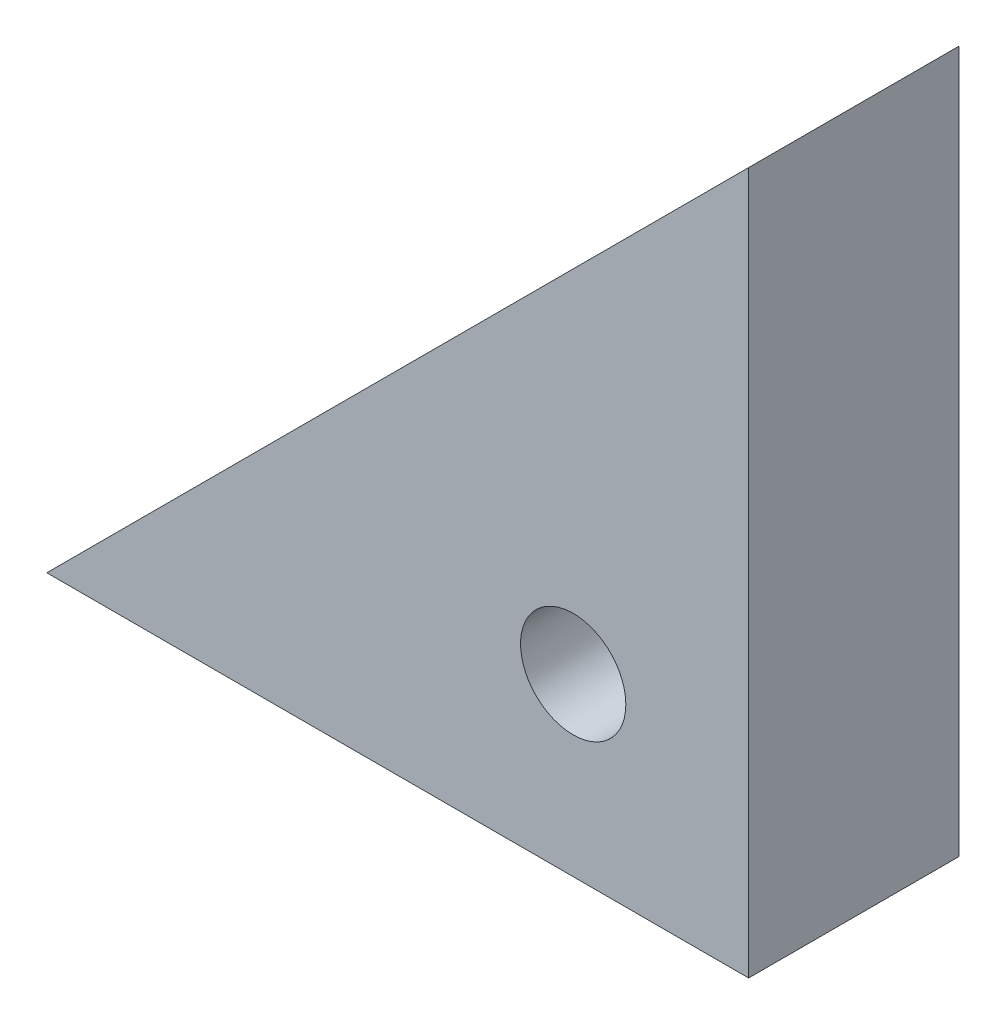
SolidWorks part; units mm, degrees
material "MDF"
ref_plane "Plano frontal" through (0, 0, 0) normal (0, 0, 1) x (1, 0, 0)
ref_plane "Plano superior" through (0, 0, 0) normal (0, 1, 0) x (1, 0, 0)
ref_plane "Plano direito" through (0, 0, 0) normal (1, 0, 0) x (0, 0, -1)
sketch "Esboço1" plane through (0, 0, 0) normal (0, 0, 1) x (1, 0, 0)
  line L0 (-10, 0) -> (10, 0)
  line L1 (10, 0) -> (10, 20)
  line L2 (10, 20) -> (-10, 0)
  line L3 (10, 0) -> (0, 10) construction
  circle A0 centre (5, 5) radius 1.5
  dimension "D3" = 3
  dimension "D1" = 10
  dimension "D2" = 10
extrude "Ressalto-extrusão1" add sketch "Esboço1" along normal blind 6
